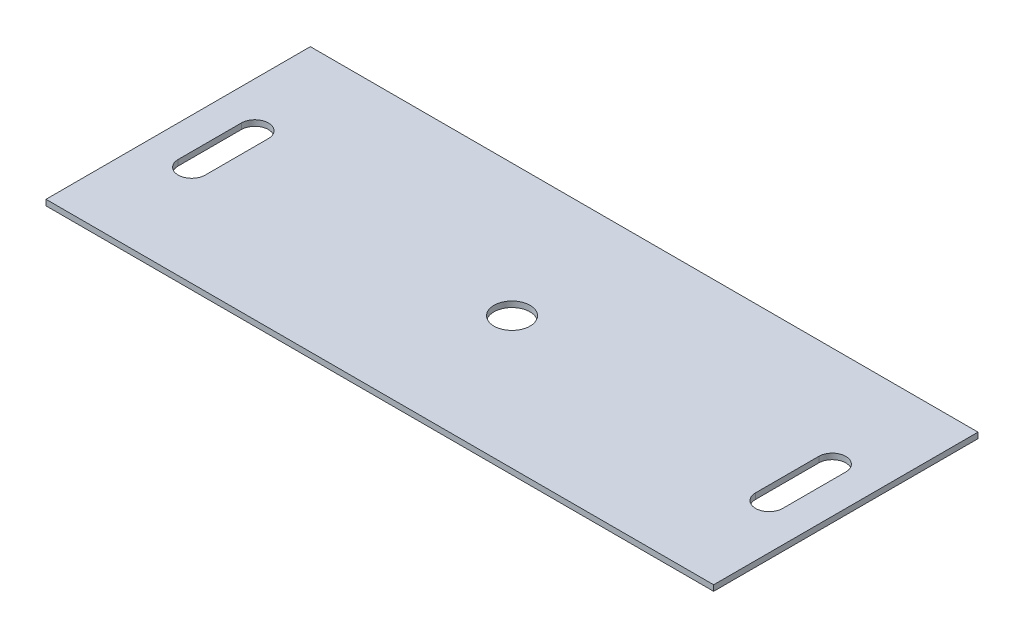
SolidWorks part; units mm, degrees
material "Acrylic (Medium-high impact)"
ref_plane "Front Plane" through (0, 0, 0) normal (0, 0, 1) x (1, 0, 0)
ref_plane "Top Plane" through (0, 0, 0) normal (0, 1, 0) x (1, 0, 0)
ref_plane "Right Plane" through (0, 0, 0) normal (1, 0, 0) x (0, 0, -1)
sketch "Sketch1" plane through (0, 0, 0) normal (0, 1, 0) x (1, 0, 0)
  line L1 (-370, -146.5) -> (370, -146.5)
  line L2 (-370, -146.5) -> (-370, 146.5)
  line L3 (-370, 146.5) -> (370, 146.5)
  line L4 (370, -146.5) -> (370, 146.5)
  line L5 (-370, -146.5) -> (370, 146.5) construction
  line L6 (-370, 146.5) -> (370, -146.5) construction
  point P0 (0, 0)
  dimension "D1" = 740
  dimension "D2" = 293
extrude "Base" add sketch "Sketch1" along normal blind 6.35
sketch "Sketch2" plane through (0, 6.35, 0) normal (0, 1, 0) x (1, 0, 0)
  line L0 (-320, -35) -> (-320, 35) construction
  line L1 (-335, -35) -> (-335, 35)
  line L2 (-305, -35) -> (-305, 35)
  line L3 (-1000, 0) -> (49000, 0) construction
  line L4 (-370, 146.5) -> (-370, -146.5) construction
  line L5 (0, -1000) -> (0, 49000) construction
  line L6 (320, -35) -> (320, 35) construction
  line L7 (335, -35) -> (335, 35)
  line L8 (305, -35) -> (305, 35)
  arc A0 (-335, -35) -> (-305, -35) centre (-320, -35) ccw
  arc A1 (-305, 35) -> (-335, 35) centre (-320, 35) ccw
  arc A2 (335, -35) -> (305, -35) centre (320, -35) cw
  arc A3 (305, 35) -> (335, 35) centre (320, 35) cw
  point P2 (-320, 0)
  point P16 (320, 0)
  dimension "D3" = 100
  dimension "D1" = 50
  dimension "D2" = 30
extrude "Handles" cut sketch "Sketch2" against normal through all
sketch "Sketch3" plane through (0, 6.35, 0) normal (0, 1, 0) x (1, 0, 0)
  circle A0 centre (0, 0) radius 20
  dimension "D1" = 40
extrude "Camera Hole" cut sketch "Sketch3" against normal through all
sketch "Sketch4" plane through (0, 6.35, 0) normal (0, 1, 0) x (1, 0, 0)
  line L0 (-130, -989.2343) -> (-130, 49010.7657) construction
  line L1 (-370, 146.5) -> (-370, -146.5) construction
  dimension "D1" = 240
